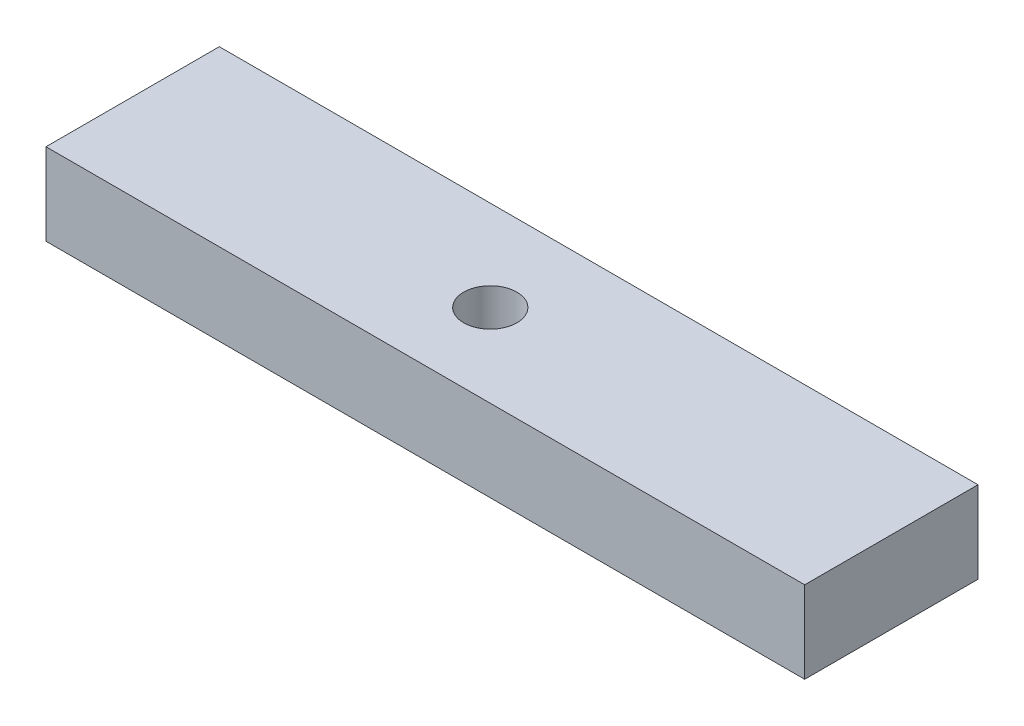
SolidWorks part; units mm, degrees
ref_plane "Front Plane" through (0, 0, 0) normal (0, 0, 1) x (1, 0, 0)
ref_plane "Top Plane" through (0, 0, 0) normal (0, 1, 0) x (1, 0, 0)
ref_plane "Right Plane" through (0, 0, 0) normal (1, 0, 0) x (0, 0, -1)
sketch "Sketch1" plane through (0, 0, 0) normal (0, 1, 0) x (1, 0, 0)
  line L1 (-21.008, 0) -> (34.592, 0)
  line L2 (-21.008, 0) -> (-21.008, -12.7)
  line L3 (-21.008, -12.7) -> (34.592, -12.7)
  line L4 (34.592, 0) -> (34.592, -12.7)
  dimension "D1" = 55.6
  dimension "D2" = 12.7
extrude "Boss-Extrude1" add sketch "Sketch1" along normal blind 6
sketch "Sketch2" plane through (0, 6, 0) normal (0, 1, 0) x (1, 0, 0)
  circle A0 centre (5.4716, -6.6209) radius 1.95
extrude "Cut-Extrude1" cut sketch "Sketch2" against normal up to surface (6 mm away) up to face at (6.792, 0, 6.35)
